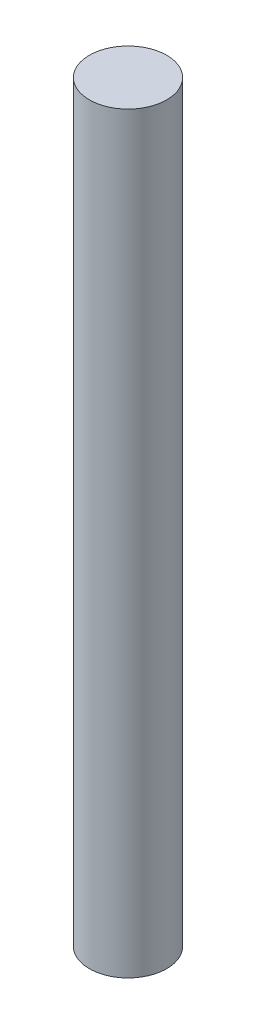
SolidWorks part; units mm, degrees
ref_plane "Plano frontal" through (0, 0, 0) normal (0, 0, 1) x (1, 0, 0)
ref_plane "Plano superior" through (0, 0, 0) normal (0, 1, 0) x (1, 0, 0)
ref_plane "Plano direito" through (0, 0, 0) normal (1, 0, 0) x (0, 0, -1)
sketch "Esboço1" plane through (0, 0, 0) normal (0, 1, 0) x (1, 0, 0)
  circle A0 centre (0, 0) radius 1.5825
  dimension "D1" = 3.165
extrude "Ressalto-extrusão1" add sketch "Esboço1" along normal blind 30.8
